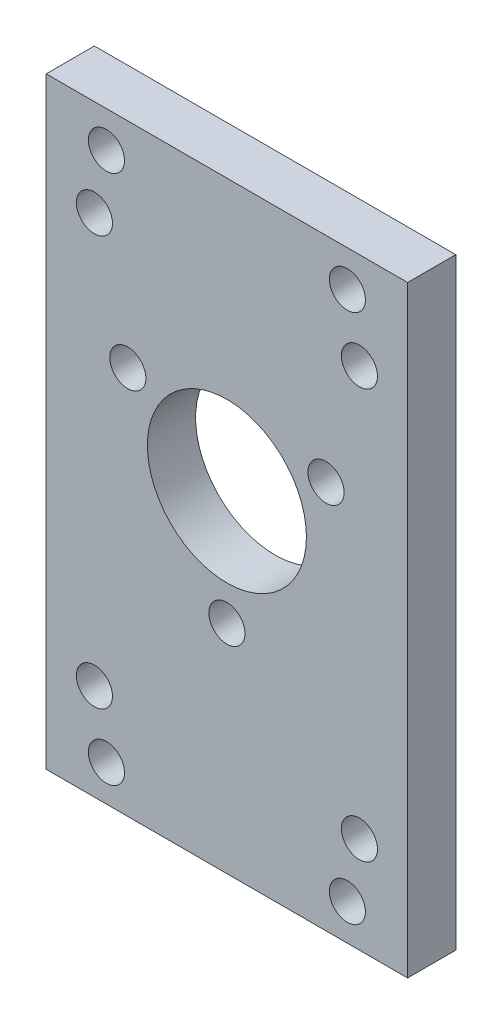
SolidWorks part; units mm, degrees
ref_plane "前视基准面" through (0, 0, 0) normal (0, 0, 1) x (1, 0, 0)
ref_plane "上视基准面" through (0, 0, 0) normal (0, 1, 0) x (1, 0, 0)
ref_plane "右视基准面" through (0, 0, 0) normal (1, 0, 0) x (0, 0, -1)
sketch "草图1" plane through (0, 0, 0) normal (0, 0, 1) x (1, 0, 0)
  line L0 (15, 50) -> (15, 0) construction
  line L1 (0, 0) -> (30, 0)
  line L2 (0, 0) -> (0, 50)
  line L3 (0, 50) -> (30, 50)
  line L4 (30, 0) -> (30, 50)
  line L5 (5, 47) -> (25, 47) construction
  line L6 (5, 3) -> (25, 3) construction
  circle A0 centre (15, 27.5) radius 6.6
  circle A1 centre (15, 27.5) radius 9.5 construction
  circle A2 centre (23.2272, 32.25) radius 1.5
  circle A3 centre (15, 18) radius 1.5
  circle A4 centre (6.7728, 32.25) radius 1.5
  circle A5 centre (5, 47) radius 1.5
  circle A6 centre (25, 47) radius 1.5
  circle A7 centre (5, 3) radius 1.5
  circle A8 centre (25, 3) radius 1.5
  point P26 (15, 47)
  dimension "D2" = 13.2
  dimension "D3" = 19
  dimension "D4" = 3
  dimension "D7" = 3
  dimension "D8" = 3
  dimension "D1" = 50
  dimension "D5" = 27.5
  dimension "D6" = 30
  dimension "D9" = 3
  dimension "D10" = 3
  dimension "D11" = 20
extrude "凸台-拉伸1" add sketch "草图1" along normal blind 4
sketch "草图2" plane through (0, 0, 4) normal (0, 0, 1) x (1, 0, 0)
  line L0 (0, 50) -> (0, 0) construction
  line L1 (4, 42) -> (26, 42) construction
  line L2 (4, 42) -> (4, 8) construction
  line L3 (4, 8) -> (26, 8) construction
  line L4 (26, 42) -> (26, 8) construction
  line L5 (30, 0) -> (30, 50) construction
  line L6 (30, 50) -> (0, 50) construction
  line L7 (0, 0) -> (30, 0) construction
  circle A0 centre (4, 42) radius 1.5
  circle A1 centre (26, 42) radius 1.5
  circle A2 centre (26, 8) radius 1.5
  circle A3 centre (4, 8) radius 1.5
  dimension "D5" = 3
  dimension "D1" = 4
  dimension "D2" = 4
  dimension "D3" = 8
  dimension "D4" = 8
extrude "切除-拉伸1" cut sketch "草图2" against normal through all
